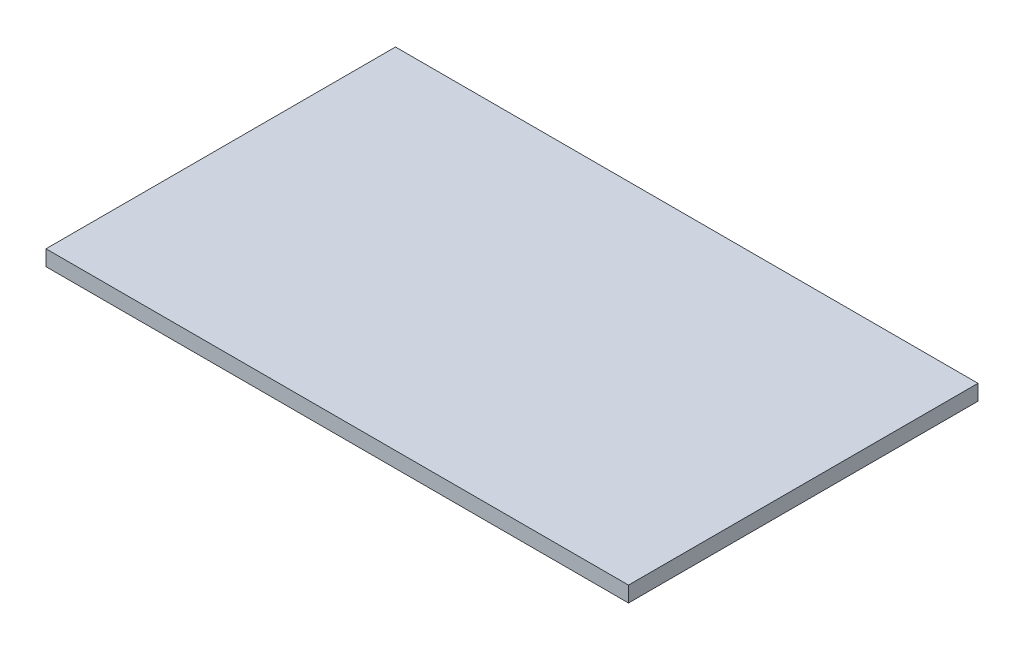
SolidWorks part; units mm, degrees
material "黑"
ref_plane "前视基准面" through (0, 0, 0) normal (0, 0, 1) x (1, 0, 0)
ref_plane "上视基准面" through (0, 0, 0) normal (0, 1, 0) x (1, 0, 0)
ref_plane "右视基准面" through (0, 0, 0) normal (1, 0, 0) x (0, 0, -1)
other "Configuration Table"
sketch "草图1" plane through (0, 0, 0) normal (0, 1, 0) x (1, 0, 0)
  line L1 (37.5, -22.5) -> (-37.5, -22.5)
  line L2 (37.5, -22.5) -> (37.5, 22.5)
  line L3 (37.5, 22.5) -> (-37.5, 22.5)
  line L4 (-37.5, -22.5) -> (-37.5, 22.5)
  line L5 (37.5, -22.5) -> (-37.5, 22.5) construction
  line L6 (37.5, 22.5) -> (-37.5, -22.5) construction
  point P0 (0, 0)
extrude "凸台-拉伸1" add sketch "草图1" along normal blind 2
